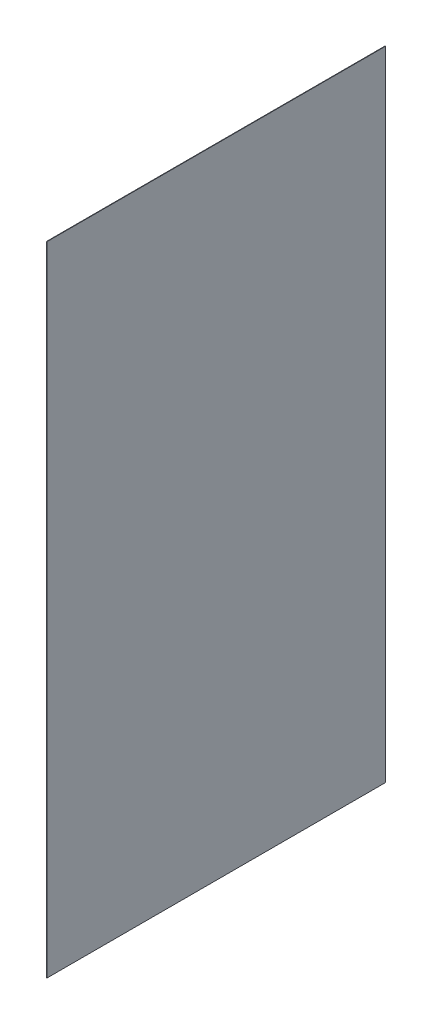
SolidWorks part; units mm, degrees
ref_plane "Front Plane" through (0, 0, 0) normal (0, 0, 1) x (1, 0, 0)
ref_plane "Top Plane" through (0, 0, 0) normal (0, 1, 0) x (1, 0, 0)
ref_plane "Right Plane" through (0, 0, 0) normal (1, 0, 0) x (0, 0, -1)
other "Configuration Table"
sketch "Sketch1" plane through (0, 0, 0) normal (0, 0, 1) x (1, 0, 0)
  line L1 (690, 182.5) -> (691, 182.5)
  line L2 (690, 182.5) -> (690, 1610)
  line L3 (690, 1610) -> (691, 1610)
  line L4 (691, 182.5) -> (691, 1610)
extrude "STORE_orta_bolme_sac_sol_1" add sketch "Sketch1" against normal blind 757.5 separate body
